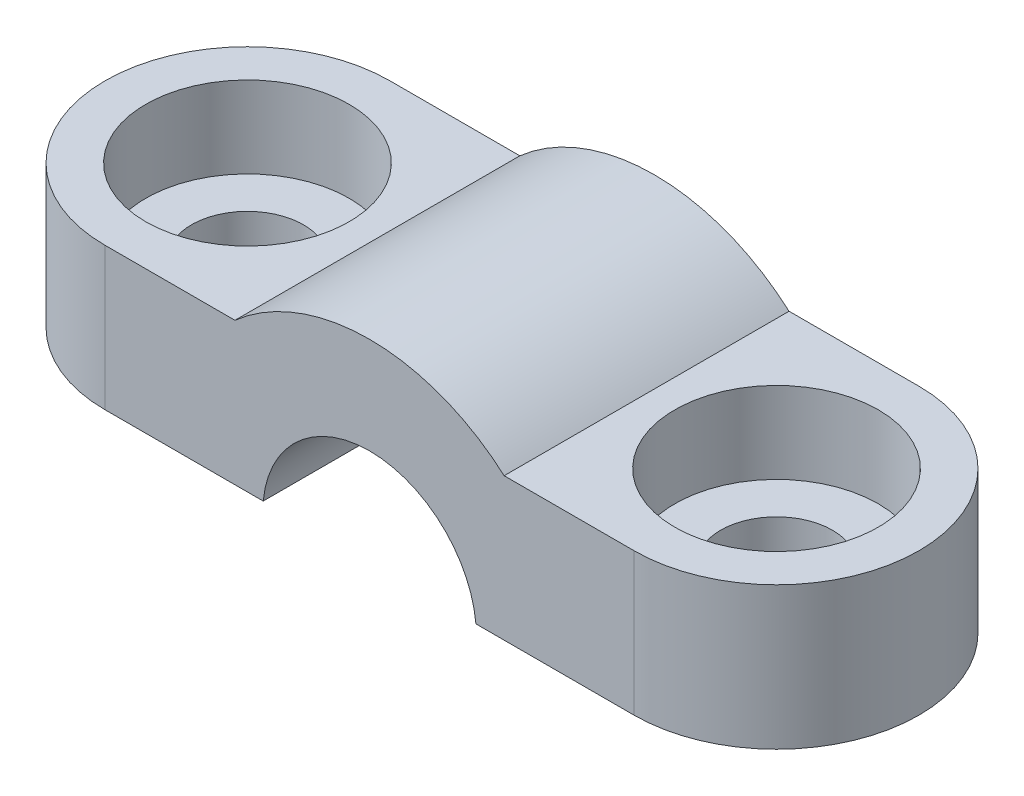
SolidWorks part; units mm, degrees
ref_plane "Front Plane" through (0, 0, 0) normal (0, 0, 1) x (1, 0, 0)
ref_plane "Top Plane" through (0, 0, 0) normal (0, 1, 0) x (1, 0, 0)
ref_plane "Right Plane" through (0, 0, 0) normal (1, 0, 0) x (0, 0, -1)
sketch "Sketch1" plane through (0, 0, 0) normal (0, 1, 0) x (1, 0, 0)
  line L1 (-13, 0) -> (13, 0)
  line L2 (-13, 0) -> (-13, 14) construction
  line L3 (-13, 14) -> (13, 14)
  line L4 (13, 0) -> (13, 14) construction
  arc A0 (-13, 14) -> (-13, 0) centre (-13, 7) ccw
  arc A1 (13, 14) -> (13, 0) centre (13, 7) cw
  point P4 (0, 0)
  dimension "D1" = 14
  dimension "D2" = 26
extrude "Boss-Extrude1" add sketch "Sketch1" along normal blind 7
sketch "Sketch2" plane through (0, 7, 0) normal (0, 1, 0) x (1, 0, 0)
  line L0 (0, 0) -> (0, 14) construction
  line L1 (13, 14) -> (-13, 14) construction
  circle A0 centre (-13, 7) radius 2.75
  arc A1 (-13, 14) -> (-13, 0) centre (-13, 7) ccw construction
  circle A2 centre (13, 7) radius 2.75
  dimension "D1" = 5.5
extrude "Cut-Extrude1" cut sketch "Sketch2" against normal through all
sketch "Sketch3" plane through (0, 7, 0) normal (0, 1, 0) x (1, 0, 0)
  line L0 (0, 14) -> (0, 0) construction
  line L1 (13, 14) -> (-13, 14) construction
  circle A0 centre (-13, 7) radius 5
  circle A1 centre (-13, 7) radius 2.75 construction
  circle A2 centre (13, 7) radius 5
  dimension "D1" = 10
extrude "Cut-Extrude2" cut sketch "Sketch3" against normal blind 4
sketch "Sketch4" plane through (0, 0, 0) normal (0, 0, 1) x (1, 0, 0)
  circle A0 centre (0, -0.5) radius 5.25
  point P2 (0, 4.75)
  dimension "D1" = 10.5
  dimension "D2" = 4.75
extrude "Cut-Extrude3" cut sketch "Sketch4" against normal through all
sketch "Sketch5" plane through (0, 0, 0) normal (0, 0, 1) x (1, 0, 0)
  line L0 (-13, 7) -> (13, 7) construction
  line L1 (-6.6144, 7) -> (6.6144, 7)
  arc A0 (6.6144, 7) -> (-6.6144, 7) centre (0, -0.5) ccw
  arc A1 (5.2261, 0) -> (-5.2261, 0) centre (0, -0.5) ccw construction
  point P5 (0, 9.5)
  point P6 (0, 4.75)
  point P7 (-6.6144, 7)
  point P8 (6.6144, 7)
  dimension "D1" = 4.75
extrude "Boss-Extrude2" add sketch "Sketch5" against normal up to surface (14 mm away) up to face at (0, 3.125, -14)
